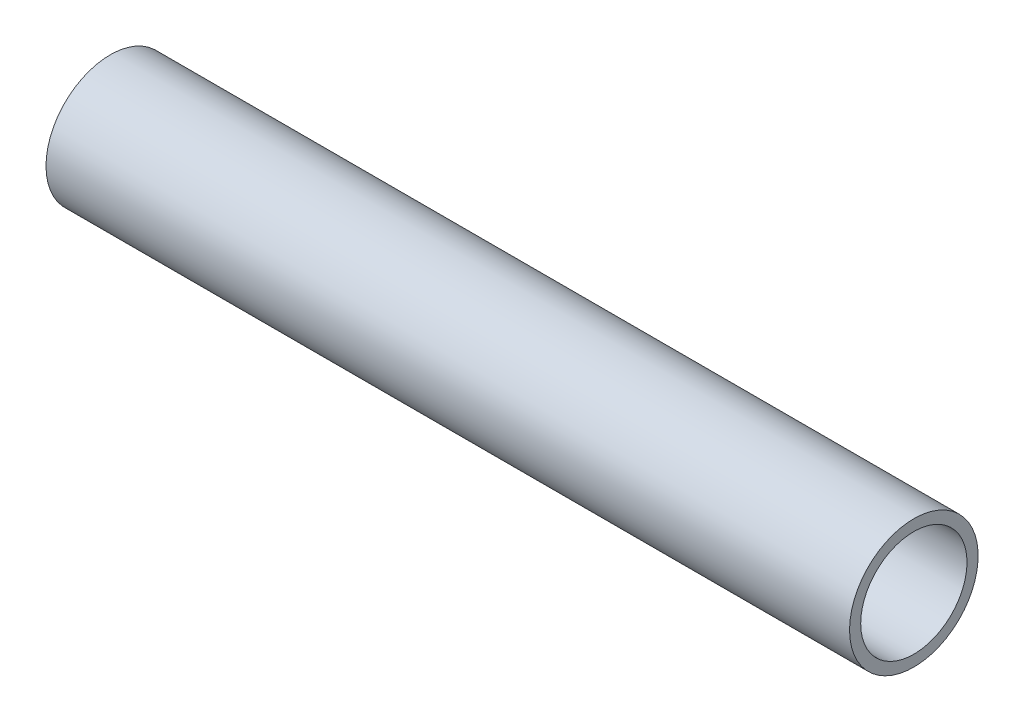
SolidWorks part; units mm, degrees
material "20"
ref_plane "前视基准面" through (0, 0, 0) normal (0, 0, 1) x (1, 0, 0)
ref_plane "上视基准面" through (0, 0, 0) normal (0, 1, 0) x (1, 0, 0)
ref_plane "右视基准面" through (0, 0, 0) normal (1, 0, 0) x (0, 0, -1)
sketch "草图1" plane through (0, 0, 0) normal (1, 0, 0) x (0, 0, -1)
  circle A0 centre (0, 0) radius 50.8
  circle A1 centre (0, 0) radius 42
  dimension "D1" = 101.6
  dimension "D2" = 84
extrude "凸台-拉伸1" add sketch "草图1" along normal mid plane 635
